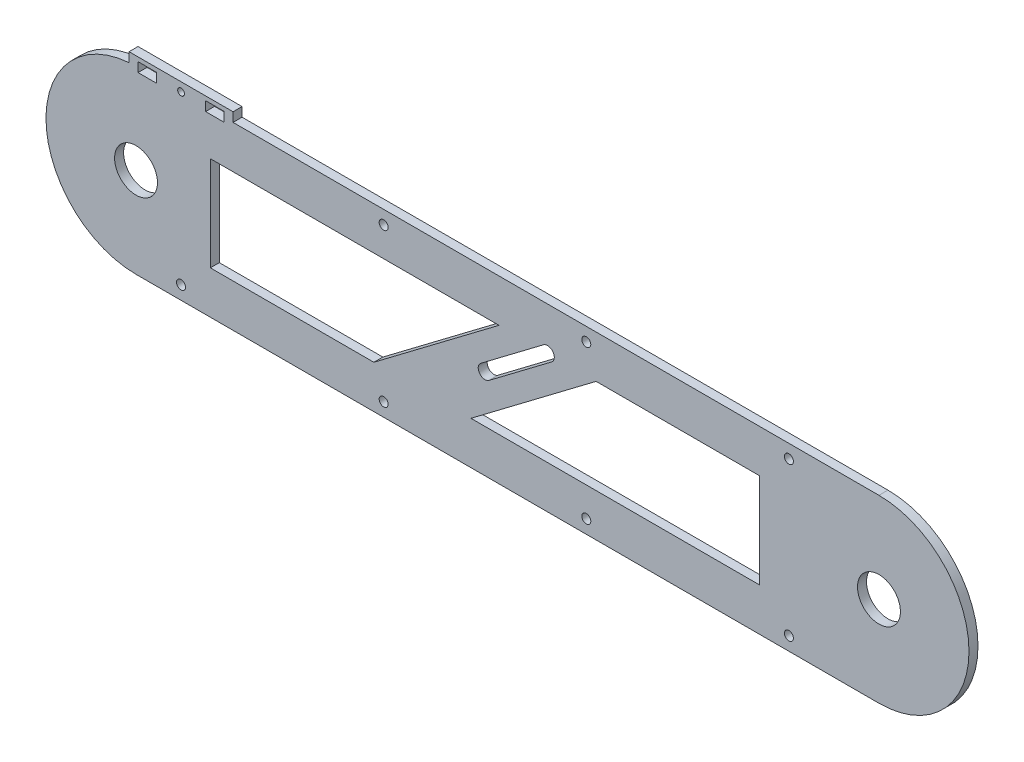
SolidWorks part; units mm, degrees
ref_plane "前视基准面" through (0, 0, 0) normal (0, 0, 1) x (1, 0, 0)
ref_plane "上视基准面" through (0, 0, 0) normal (0, 1, 0) x (1, 0, 0)
ref_plane "右视基准面" through (0, 0, 0) normal (1, 0, 0) x (0, 0, -1)
sketch "草图1" plane through (0, 0, 0) normal (0, 0, 1) x (1, 0, 0)
  line L0 (328.5429, -0.1457) -> (-1.4571, -0.1457) construction
  line L8 (328.5429, -40.1457) -> (-1.4571, -40.1457)
  line L9 (-1.4571, 39.8543) -> (328.5429, 39.8543)
  circle A0 centre (-1.4571, -0.1457) radius 9.53
  circle A1 centre (-1.4571, -0.1457) radius 40 construction
  arc A4 (-1.4571, 39.8543) -> (-1.4571, -40.1457) centre (-1.4571, -0.1457) ccw
  circle A11 centre (328.5429, -0.1457) radius 9.53
  circle A12 centre (328.5429, -0.1457) radius 40 construction
  circle A16 centre (328.5429, -0.1457) radius 30 construction
  arc A20 (328.5429, 39.8543) -> (328.5429, -40.1457) centre (328.5429, -0.1457) cw
  dimension "D1" = 330
  dimension "D2" = 19.06
  dimension "D4" = 19.06
  dimension "D5" = 80
extrude "凸台-拉伸1" add sketch "草图1" along normal blind 4
sketch "草图4" plane through (0, 0, 4) normal (0, 0, 1) x (1, 0, 0)
  line L1 (328.5429, 39.8543) -> (-1.4571, 39.8543) construction
  line L2 (41.6429, 35.3514) -> (-4.5571, 35.3514)
  line L3 (41.6429, 35.3514) -> (41.6429, 43.9543)
  line L4 (41.6429, 43.9543) -> (-4.5571, 43.9543)
  line L5 (-4.5571, 35.3514) -> (-4.5571, 43.9543)
  dimension "D1" = 46.2
  dimension "D2" = 3.1
  dimension "D3" = 4.1
extrude "凸台-拉伸2" add sketch "草图4" against normal blind 4
sketch "草图2" plane through (0, 0, 4) normal (0, 0, 1) x (1, 0, 0)
  line L0 (198.5429, 33.8543) -> (288.5429, 33.8543) construction
  line L1 (18.5429, 33.8543) -> (198.5429, 33.8543) construction
  line L2 (108.5429, -34.1457) -> (198.5429, 33.8543) construction
  line L3 (18.5429, 33.8543) -> (18.5429, -34.1457) construction
  line L4 (18.5429, -34.1457) -> (108.5429, -34.1457) construction
  line L5 (31.5429, -21.1457) -> (104.1839, -21.1457)
  line L6 (104.1839, -21.1457) -> (159.7721, 20.8543)
  line L7 (31.5429, 20.8543) -> (159.7721, 20.8543)
  line L8 (31.5429, 20.8543) -> (31.5429, -21.1457)
  line L9 (108.5429, -34.1457) -> (288.5429, -34.1457) construction
  line L10 (288.5429, -34.1457) -> (288.5429, 33.8543) construction
  line L12 (275.5429, 20.8543) -> (202.9018, 20.8543)
  line L13 (147.3136, -21.1457) -> (202.9018, 20.8543)
  line L14 (147.3136, -21.1457) -> (275.5429, -21.1457)
  line L15 (275.5429, -21.1457) -> (275.5429, 20.8543)
  line L20 (18.5429, 33.8543) -> (18.5429, 39.8543) construction
  line L28 (288.5429, 33.8543) -> (198.5429, 33.8543) construction
  line L30 (328.5429, 39.8543) -> (41.6429, 39.8543) construction
  line L31 (7.6429, 37.9143) -> (-0.5571, 42.1143) construction
  line L36 (29.4429, 42.1143) -> (37.6429, 42.1143)
  line L37 (29.4429, 42.1143) -> (29.4429, 37.9143)
  line L38 (29.4429, 37.9143) -> (37.6429, 37.9143)
  line L39 (37.6429, 42.1143) -> (37.6429, 37.9143)
  line L40 (29.4429, 42.1143) -> (37.6429, 37.9143) construction
  line L41 (29.4429, 37.9143) -> (37.6429, 42.1143) construction
  line L42 (7.6429, 42.1143) -> (-0.5571, 37.9143) construction
  line L43 (18.5429, 33.8543) -> (-161.4571, 33.8543) construction
  line L44 (-0.5571, 42.1143) -> (-0.5571, 37.9143)
  line L45 (7.6429, 37.9143) -> (-0.5571, 37.9143)
  line L46 (7.6429, 42.1143) -> (7.6429, 37.9143)
  line L47 (7.6429, 42.1143) -> (-0.5571, 42.1143)
  circle A1 centre (108.5429, 33.8543) radius 2
  circle A2 centre (198.5429, 33.8543) radius 2
  circle A3 centre (288.5429, 33.8543) radius 2
  circle A4 centre (108.5429, -34.1457) radius 2
  circle A5 centre (198.5429, -34.1457) radius 2
  circle A6 centre (288.5429, -34.1457) radius 2
  circle A7 centre (18.5429, -34.1457) radius 2
  circle A9 centre (18.5429, 40.0143) radius 1.5
  point P0 (3.5429, 40.0143)
  point P2 (-1.4571, -0.1457)
  point P30 (33.5429, 40.0143)
  point P42 (0, 0)
  point P43 (0, 0)
  dimension "D1" = 8.2
  dimension "D2" = 34
  dimension "D3" = 4.2
  dimension "D8" = 6.16
  dimension "D4" = 15
  dimension "D6" = 13
  dimension "D7" = 13
extrude "切除-拉伸1" cut sketch "草图2" against normal blind 4
sketch "草图3" plane through (0, 0, 4) normal (0, 0, 1) x (1, 0, 0)
  line L0 (202.9018, 20.8543) -> (159.7721, 20.8543) construction
  line L1 (147.3136, -21.1457) -> (104.1839, -21.1457) construction
  line L2 (181.337, 20.8543) -> (125.7487, -21.1457) construction
  line L3 (181.337, 20.8543) -> (153.5429, -0.1457) construction
  line L4 (183.1455, 18.4607) -> (155.3514, -2.5393)
  line L5 (179.5285, 23.2479) -> (151.7344, 2.2479)
  arc A0 (183.1455, 18.4607) -> (179.5285, 23.2479) centre (181.337, 20.8543) ccw
  arc A1 (151.7344, 2.2479) -> (155.3514, -2.5393) centre (153.5429, -0.1457) ccw
  point P11 (167.4399, 10.3543)
extrude "切除-拉伸2" cut sketch "草图3" against normal blind 10
